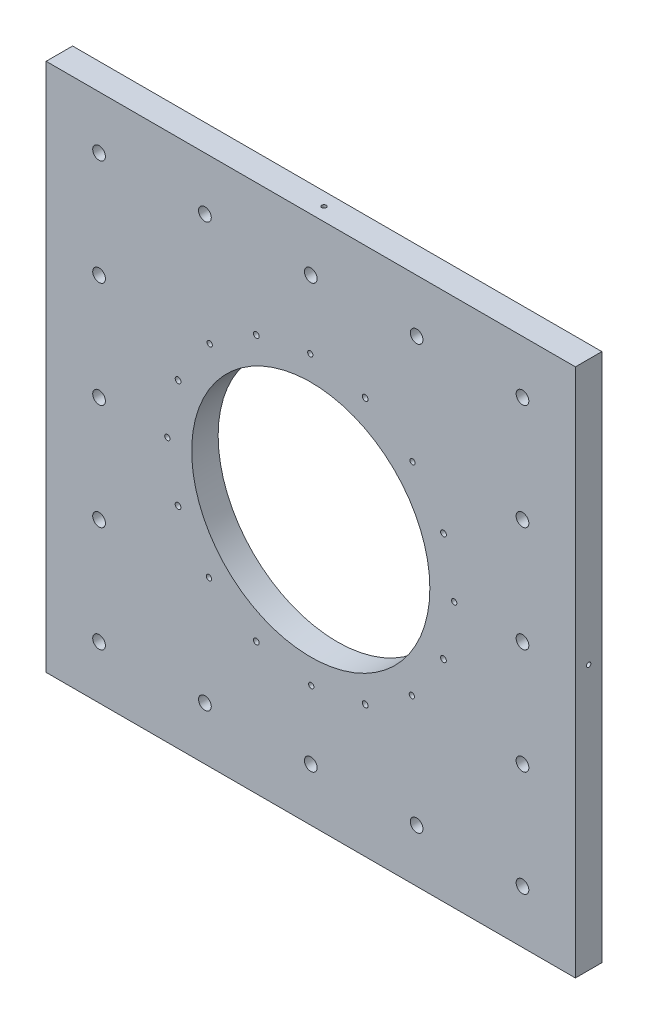
SolidWorks part; units mm, degrees
material "5052-O"
ref_plane "正面" through (0, 0, 0) normal (0, 0, 1) x (1, 0, 0)
ref_plane "平面" through (0, 0, 0) normal (0, 1, 0) x (1, 0, 0)
ref_plane "右側面" through (0, 0, 0) normal (1, 0, 0) x (0, 0, -1)
sketch "中心線" plane through (0, 0, 0) normal (1, 0, 0) x (0, 0, -1)
  line L0 (-153.0593, 0) -> (155.5873, 0) construction
ref_axis "中心軸" through (0, 0, -171.0196) along (0, 0, 1)
sketch "ｽｹｯﾁ2" plane through (0, 0, 0) normal (0, 0, 1) x (1, 0, 0)
  line L1 (-200, -200) -> (200, -200)
  line L2 (-200, -200) -> (-200, 200)
  line L3 (-200, 200) -> (200, 200)
  line L4 (200, -200) -> (200, 200)
  line L5 (-200, -200) -> (200, 200) construction
  line L6 (-200, 200) -> (200, -200) construction
  point P0 (0, 0)
  dimension "D1" = 400
  dimension "D2" = 400
sketch "ｽｹｯﾁ3" plane through (0, 0, 0) normal (0, 0, 1) x (1, 0, 0)
  point P0 (-200, 200)
  point P4 (-100, 200)
  point P5 (0, 200)
  point P6 (100, 200)
  point P7 (200, 200)
  point P8 (-100, 100)
  point P9 (0, 100)
  point P10 (100, 100)
  point P11 (200, 100)
  point P12 (-100, 0)
  point P13 (0, 0)
  point P14 (100, 0)
  point P15 (200, 0)
  point P16 (-100, -100)
  point P17 (0, -100)
  point P18 (100, -100)
  point P19 (200, -100)
  point P20 (-100, -200)
  point P21 (0, -200)
  point P22 (100, -200)
  point P23 (200, -200)
  point P24 (-200, 100)
  point P25 (-200, 0)
  point P26 (-200, -100)
  point P27 (-200, -200)
  dimension "D1" = 5
  dimension "D2" = 5
sketch "ｽｹｯﾁ4" plane through (0, 0, 0) normal (0, 0, 1) x (1, 0, 0)
  line L1 (-250, -250) -> (250, -250)
  line L2 (-250, -250) -> (-250, 250)
  line L3 (-250, 250) -> (250, 250)
  line L4 (250, -250) -> (250, 250)
  line L5 (-250, -250) -> (250, 250) construction
  line L6 (-250, 250) -> (250, -250) construction
  point P0 (0, 0)
  dimension "D1" = 500
  dimension "D2" = 500
extrude "ﾎﾞｽ - 押し出し2" add sketch "ｽｹｯﾁ4" along normal blind 25 contours L3 L4 L1 L2
sketch "ｽｹｯﾁ9" plane through (0, 0, 25) normal (0, 0, 1) x (1, 0, 0)
  circle A0 centre (0, 0) radius 112.5
  dimension "D1" = 225
extrude "ｶｯﾄ - 押し出し2" cut sketch "ｽｹｯﾁ9" against normal blind 100 contours A0
sketch "ｽｹｯﾁ8" plane through (0, 0, 0) normal (0, 0, 1) x (1, 0, 0)
  circle A0 centre (0, 0) radius 145.5
  dimension "D1" = 291
sketch "ｽｹｯﾁ20" plane through (0, 0, 25) normal (0, 0, 1) x (1, 0, 0)
  line L0 (0, 0) -> (406.8609, 0) construction
  point P5 (125.3659, 51.4163)
  point P6 (125.3659, -51.4163)
  dimension "D1" = 135.5
  dimension "D2" = 135.5
  dimension "D3" = 22.3
  dimension "D4" = 22.3
hole_wizard "1/4-28 ねじ穴2" positions "3Dｽｹｯﾁ6" profile "ｽｹｯﾁ21" tap size "1/4-28" standard "Ansi Inch" end condition through all
sketch3d "3Dｽｹｯﾁ6"
  point P0 (125.3659, 51.4163, 25)
  point P9 (125.3659, -51.4163, 25)
sketch "ｽｹｯﾁ21" plane through (125.3659, 51.4163, 25) normal (1, 0, 0) x (0, -1, 0)
  line L0 (0, 0) -> (0, 25)
  line L1 (0, 25) -> (2.7051, 25)
  line L2 (2.7051, 25) -> (2.7051, 0)
  line L5 (2.7051, 0) -> (0, 0)
  line L11 (0, -6.35) -> (0, 107.95) construction
  dimension "次ｻｰﾌｪｽまでのねじ下穴ﾄﾞﾘﾙ直径" = 5.4102
  dimension "次ｻｰﾌｪｽまでのねじ下穴ﾄﾞﾘﾙの深さ" = 25
cosmetic thread "穴のねじ山3" parameters "D2"=6.35
cosmetic thread "穴のねじ山5" parameters "D2"=6.35
pattern_circular "円形ﾊﾟﾀｰﾝ3" count 4 over 360 about axis through (0, 0, 0) along (0, 0, 1) of "1/4-28 ねじ穴2"
sketch "ｽｹｯﾁ22" plane through (0, 0, 25) normal (0, 0, 1) x (1, 0, 0)
  line L0 (0, 0) -> (209.8752, 0) construction
  line L1 (0, 0) -> (264.5715, 109.5891) construction
  point P0 (96.1468, 95.4779)
  point P4 (135.4992, 0.473)
  dimension "D1" = 22.3
  dimension "D2" = 135.5
  dimension "D3" = 22.5
  dimension "D4" = 135.5
  dimension "D5" = 22.3
hole_wizard "M6x1.0 ねじ穴2" positions "3Dｽｹｯﾁ7" profile "ｽｹｯﾁ23" tap size "M6x1.0" standard "JIS" end condition through all
sketch3d "3Dｽｹｯﾁ7"
  point P0 (96.1468, 95.4779, 25)
  point P11 (135.4992, 0.473, 25)
sketch "ｽｹｯﾁ23" plane through (96.1468, 95.4779, 25) normal (1, 0, 0) x (0, -1, 0)
  line L0 (0, 0) -> (0, 25)
  line L1 (0, 25) -> (2.5, 25)
  line L2 (2.5, 25) -> (2.5, 0)
  line L5 (2.5, 0) -> (0, 0)
  line L11 (0, -6.35) -> (0, 107.95) construction
  dimension "次ｻｰﾌｪｽまでのねじ下穴ﾄﾞﾘﾙ直径" = 5
  dimension "次ｻｰﾌｪｽまでのねじ下穴ﾄﾞﾘﾙの深さ" = 25
cosmetic thread "穴のねじ山6" parameters "D2"=6
cosmetic thread "穴のねじ山7" parameters "D2"=6
pattern_circular "円形ﾊﾟﾀｰﾝ4" count 4 over 360 about axis through (0, 0, 0) along (0, 0, 1) of "M6x1.0 ねじ穴2"
hole_wizard "M10 すきま穴3" positions "3Dｽｹｯﾁ4" profile "ｽｹｯﾁ16" hole size "M10" standard "JIS" end condition through all
sketch3d "3Dｽｹｯﾁ4"
  point P4 (200, 200, 0)
sketch "ｽｹｯﾁ16" plane through (200, 200, 0) normal (1, 0, 0) x (0, 1, 0)
  line L0 (0, 0) -> (0, 25)
  line L1 (0, 25) -> (6, 25)
  line L2 (6, 25) -> (6, 0)
  line L5 (6, 0) -> (0, 0)
  line L11 (0, -6.35) -> (0, 107.95) construction
  dimension "通し穴の直径" = 12
  dimension "通し穴の深さ" = 25
pattern_linear "直線ﾊﾟﾀｰﾝ1" count 5 spacing 100 along (-1, 0, 0) count 5 spacing 100 along (0, -1, 0) skipping (1, 1), (1, 2), (1, 3), (2, 1), (2, 2), (2, 3), (3, 1), (3, 2), (3, 3) of "M10 すきま穴3"
sketch "ｽｹｯﾁ26" plane through (-250, 0, 0) normal (-1, 0, 0) x (0, 0, 1)
  line L0 (0, 0) -> (25, 0) construction
  line L1 (25, -250) -> (25, 250) construction
  point P5 (12.5, 0)
hole_wizard "M5x0.8 ねじ穴2" positions "ｽｹｯﾁ28" profile "ｽｹｯﾁ27" tap size "M5x0.8" standard "JIS"
sketch "ｽｹｯﾁ28" plane through (-250, 0, 0) normal (-1, 0, 0) x (0, 0, 1)
  point P0 (12.5, 0)
sketch "ｽｹｯﾁ27" plane through (-250, 0, 12.5) normal (0, 1, 0) x (0, 0, 1)
  line L0 (0, 0) -> (0, 9.2618)
  line L1 (0, 9.2618) -> (2.1, 8)
  line L2 (2.1, 8) -> (2.1, 0)
  line L5 (2.1, 0) -> (0, 0)
  line L10 (0, 9.2618) -> (-2.1, 8) construction
  line L11 (0, -6.35) -> (0, 107.95) construction
  dimension "ねじ下穴ﾄﾞﾘﾙ直径" = 4.2
  dimension "ねじ下穴ﾄﾞﾘﾙの深さ" = 8
  dimension "ﾄﾞﾘﾙ角度" = 118
cosmetic thread "穴のねじ山9" parameters "D1"=4, "D2"=5
pattern_circular "円形ﾊﾟﾀｰﾝ5" count 4 over 360 about axis through (0, 0, -171.0196) along (0, 0, 1) of "M5x0.8 ねじ穴2"
